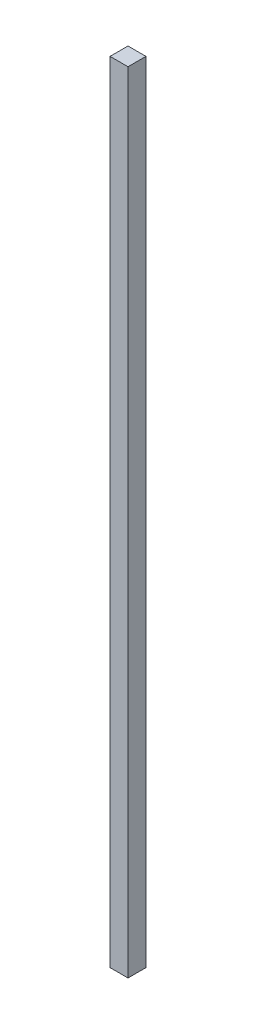
SolidWorks part; units mm, degrees
material "Balsa"
ref_plane "Front Plane" through (0, 0, 0) normal (0, 0, 1) x (1, 0, 0)
ref_plane "Top Plane" through (0, 0, 0) normal (0, 1, 0) x (1, 0, 0)
ref_plane "Right Plane" through (0, 0, 0) normal (1, 0, 0) x (0, 0, -1)
sketch "Sketch1" plane through (0, 0, 0) normal (0, 1, 0) x (1, 0, 0)
  line L1 (0, 0) -> (6.35, 0)
  line L2 (0, 0) -> (0, -6.35)
  line L3 (0, -6.35) -> (6.35, -6.35)
  line L4 (6.35, 0) -> (6.35, -6.35)
  dimension "D1" = 6.35
  dimension "0.25" = 6.35
extrude "Boss-Extrude1" add sketch "Sketch1" along normal blind 279.4
